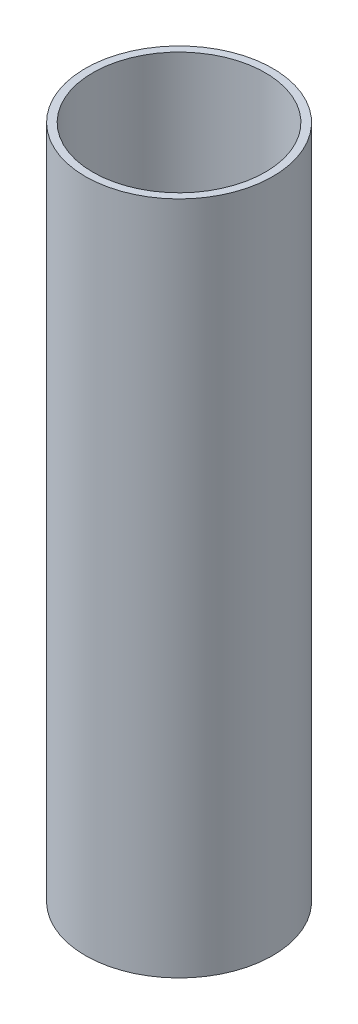
SolidWorks part; units mm, degrees
ref_plane "Front Plane" through (0, 0, 0) normal (0, 0, 1) x (1, 0, 0)
ref_plane "Top Plane" through (0, 0, 0) normal (0, 1, 0) x (1, 0, 0)
ref_plane "Right Plane" through (0, 0, 0) normal (1, 0, 0) x (0, 0, -1)
sketch "Sketch1" plane through (0, 0, 0) normal (0, 1, 0) x (1, 0, 0)
  circle A0 centre (0, 0) radius 15.875
  circle A1 centre (0, 0) radius 14.605
  dimension "D1" = 31.75
  dimension "D2" = 29.21
extrude "Boss-Extrude1" add sketch "Sketch1" along normal blind 114.3
